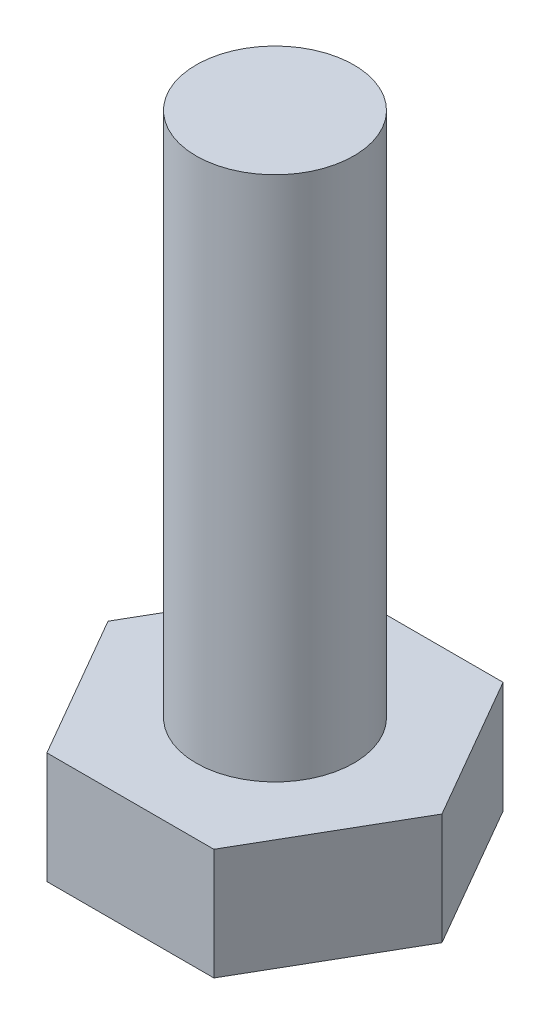
SolidWorks part; units mm, degrees
ref_plane "前视基准面" through (0, 0, 0) normal (0, 0, 1) x (1, 0, 0)
ref_plane "上视基准面" through (0, 0, 0) normal (0, 1, 0) x (1, 0, 0)
ref_plane "右视基准面" through (0, 0, 0) normal (1, 0, 0) x (0, 0, -1)
sketch "草图1" plane through (0, 0, 0) normal (0, 1, 0) x (1, 0, 0)
  circle A0 centre (0, 0) radius 1.5
  dimension "D1" = 3
extrude "凸台-拉伸1" add sketch "草图1" along normal blind 10
sketch "草图3" plane through (0, 0, 0) normal (0, -1, 0) x (1, 0, 0)
  line L1 (3.1754, 0) -> (1.5877, 2.75)
  line L2 (1.5877, 2.75) -> (-1.5877, 2.75)
  line L3 (-1.5877, 2.75) -> (-3.1754, 0)
  line L4 (-3.1754, 0) -> (-1.5877, -2.75)
  line L5 (-1.5877, -2.75) -> (1.5877, -2.75)
  line L6 (1.5877, -2.75) -> (3.1754, 0)
  circle A0 centre (0, 0) radius 2.75 construction
  dimension "D1" = 5.5
extrude "凸台-拉伸2" add sketch "草图3" along normal blind 2.12 contours L5 L6 L1 L2 L3 L4
